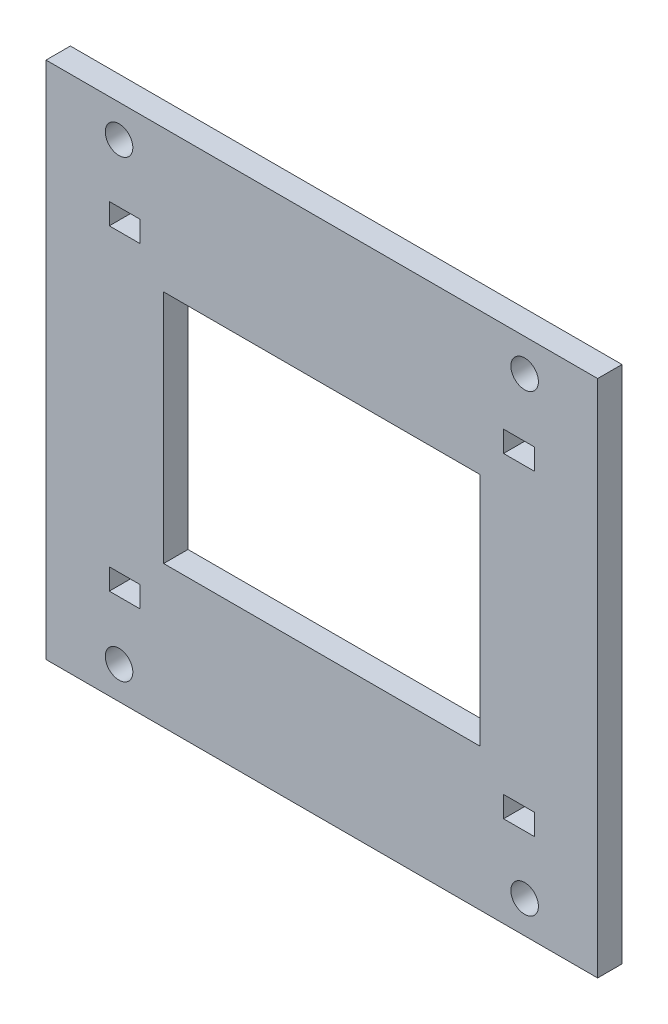
SolidWorks part; units mm, degrees
ref_plane "前视基准面" through (0, 0, 0) normal (0, 0, 1) x (1, 0, 0)
ref_plane "上视基准面" through (0, 0, 0) normal (0, 1, 0) x (1, 0, 0)
ref_plane "右视基准面" through (0, 0, 0) normal (1, 0, 0) x (0, 0, -1)
other "Configuration Table"
sketch "草图1" plane through (0, 0, 0) normal (0, 0, 1) x (1, 0, 0)
  line L0 (-34, -32) -> (34, -32)
  line L1 (34, -32) -> (34, 32)
  line L2 (34, 32) -> (-34, 32)
  line L3 (-34, 32) -> (-34, -32)
extrude "Board_mount_base" add sketch "草图1" along normal blind 3 from offset 0
sketch "草图2" plane through (0, 0, 0) normal (0, 0, 1) x (1, 0, 0)
  line L0 (-19.5, -14.5) -> (19.5, -14.5)
  line L1 (19.5, -14.5) -> (19.5, 14.5)
  line L2 (19.5, 14.5) -> (-19.5, 14.5)
  line L3 (-19.5, 14.5) -> (-19.5, -14.5)
extrude "Solder_and_connector_opening" cut sketch "草图2" along normal blind 3.2 from offset 0.1
sketch "草图3" plane through (0, 0, 0) normal (0, 0, 1) x (1, 0, 0)
  line L0 (-26.2, -20.8) -> (-22.4, -20.8)
  line L1 (-22.4, -20.8) -> (-22.4, -18.2)
  line L2 (-22.4, -18.2) -> (-26.2, -18.2)
  line L3 (-26.2, -18.2) -> (-26.2, -20.8)
  line L4 (-26.2, 18.2) -> (-22.4, 18.2)
  line L5 (-22.4, 18.2) -> (-22.4, 20.8)
  line L6 (-22.4, 20.8) -> (-26.2, 20.8)
  line L7 (-26.2, 20.8) -> (-26.2, 18.2)
  line L8 (22.4, -20.8) -> (26.2, -20.8)
  line L9 (26.2, -20.8) -> (26.2, -18.2)
  line L10 (26.2, -18.2) -> (22.4, -18.2)
  line L11 (22.4, -18.2) -> (22.4, -20.8)
  line L12 (22.4, 18.2) -> (26.2, 18.2)
  line L13 (26.2, 18.2) -> (26.2, 20.8)
  line L14 (26.2, 20.8) -> (22.4, 20.8)
  line L15 (22.4, 20.8) -> (22.4, 18.2)
extrude "PCB_M2_slots_centres48p6x39" cut sketch "草图3" along normal blind 3.2 from offset 0.1
sketch "草图4" plane through (0, 0, 0) normal (0, 0, 1) x (1, 0, 0)
  circle A0 centre (-25, -28) radius 1.7
  circle A1 centre (-25, 28) radius 1.7
  circle A2 centre (25, -28) radius 1.7
  circle A3 centre (25, 28) radius 1.7
extrude "Deck_attachment_M3" cut sketch "草图4" along normal blind 3.2 from offset 0.1
